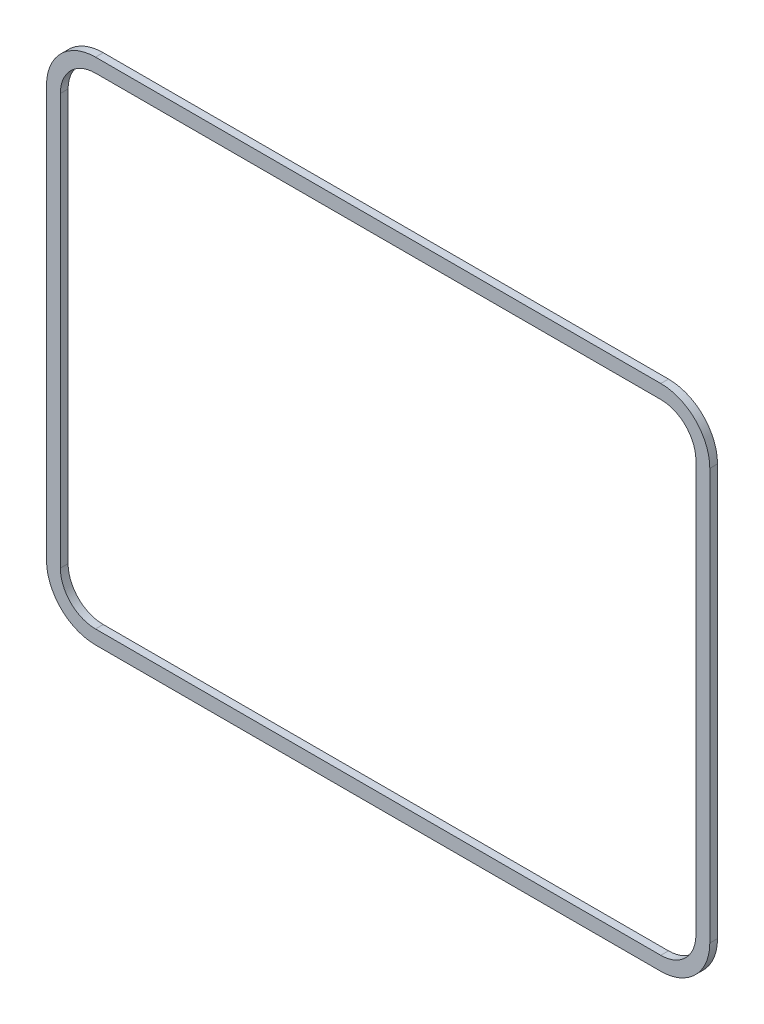
SolidWorks part; units mm, degrees
ref_plane "Front Plane" through (0, 0, 0) normal (0, 0, 1) x (1, 0, 0)
ref_plane "Top Plane" through (0, 0, 0) normal (0, 1, 0) x (1, 0, 0)
ref_plane "Right Plane" through (0, 0, 0) normal (1, 0, 0) x (0, 0, -1)
sketch "Sketch1" plane through (0, 0, 0) normal (0, 0, 1) x (1, 0, 0)
  line L0 (-109.7534, -66.7) -> (-109.7534, 67.7) construction
  line L1 (93.1, -84.3534) -> (-92.1, -84.3534) construction
  line L2 (109.7534, -66.7) -> (109.7534, 67.7) construction
  line L3 (92.1, 84.3534) -> (-93.1, 84.3534) construction
  line L4 (-109.7534, -66.7) -> (-109.7534, 67.7) construction
  line L5 (93.1, -84.3534) -> (-92.1, -84.3534) construction
  line L6 (109.7534, -66.7) -> (109.7534, 67.7) construction
  line L7 (92.1, 84.3534) -> (-93.1, 84.3534) construction
  line L8 (92.1, 84.3534) -> (93.1, 84.3534) construction
  line L9 (109.7534, -67.7) -> (109.7534, -66.7) construction
  line L10 (-93.1, -84.3534) -> (-92.1, -84.3534) construction
  line L11 (-109.7534, -67.7) -> (-109.7534, -66.7) construction
  line L12 (-104.6734, -66.7) -> (-104.6734, 67.7)
  line L13 (-104.6734, -67.7) -> (-104.6734, -66.7)
  line L14 (-93.1, -79.2734) -> (-92.1, -79.2734)
  line L15 (93.1, -79.2734) -> (-92.1, -79.2734)
  line L16 (104.6734, -67.7) -> (104.6734, -66.7)
  line L17 (104.6734, -66.7) -> (104.6734, 67.7)
  line L18 (92.1, 79.2734) -> (93.1, 79.2734)
  line L19 (92.1, 79.2734) -> (-93.1, 79.2734)
  line L20 (-109.2454, -66.7) -> (-109.2454, 67.7)
  line L21 (-109.2454, -67.7) -> (-109.2454, -66.7)
  line L22 (-93.1, -83.8454) -> (-92.1, -83.8454)
  line L23 (93.1, -83.8454) -> (-92.1, -83.8454)
  line L24 (109.2454, -67.7) -> (109.2454, -66.7)
  line L25 (109.2454, -66.7) -> (109.2454, 67.7)
  line L26 (92.1, 83.8454) -> (93.1, 83.8454)
  line L27 (92.1, 83.8454) -> (-93.1, 83.8454)
  arc A0 (-109.7534, -67.7) -> (-93.1, -84.3534) centre (-93.1, -67.7) ccw construction
  arc A1 (93.1, -84.3534) -> (109.7534, -67.7) centre (93.1, -67.7) ccw construction
  arc A2 (109.7534, 67.7) -> (93.1, 84.3534) centre (93.1, 67.7) ccw construction
  arc A3 (-93.1, 84.3534) -> (-109.7534, 67.7) centre (-93.1, 67.7) ccw construction
  arc A4 (-109.7534, -67.7) -> (-93.1, -84.3534) centre (-93.1, -67.7) ccw construction
  arc A5 (93.1, -84.3534) -> (109.7534, -67.7) centre (93.1, -67.7) ccw construction
  arc A6 (109.7534, 67.7) -> (93.1, 84.3534) centre (93.1, 67.7) ccw construction
  arc A7 (-93.1, 84.3534) -> (-109.7534, 67.7) centre (-93.1, 67.7) ccw construction
  arc A8 (-93.1, 79.2734) -> (-104.6734, 67.7) centre (-93.1, 67.7) ccw
  arc A9 (-104.6734, -67.7) -> (-93.1, -79.2734) centre (-93.1, -67.7) ccw
  arc A10 (93.1, -79.2734) -> (104.6734, -67.7) centre (93.1, -67.7) ccw
  arc A11 (104.6734, 67.7) -> (93.1, 79.2734) centre (93.1, 67.7) ccw
  arc A12 (-93.1, 83.8454) -> (-109.2454, 67.7) centre (-93.1, 67.7) ccw
  arc A13 (-109.2454, -67.7) -> (-93.1, -83.8454) centre (-93.1, -67.7) ccw
  arc A14 (93.1, -83.8454) -> (109.2454, -67.7) centre (93.1, -67.7) ccw
  arc A15 (109.2454, 67.7) -> (93.1, 83.8454) centre (93.1, 67.7) ccw
  dimension "D1" = 5.08
  dimension "D2" = 0.508
extrude "Boss-Extrude1" add sketch "Sketch1" against normal blind 2.54
